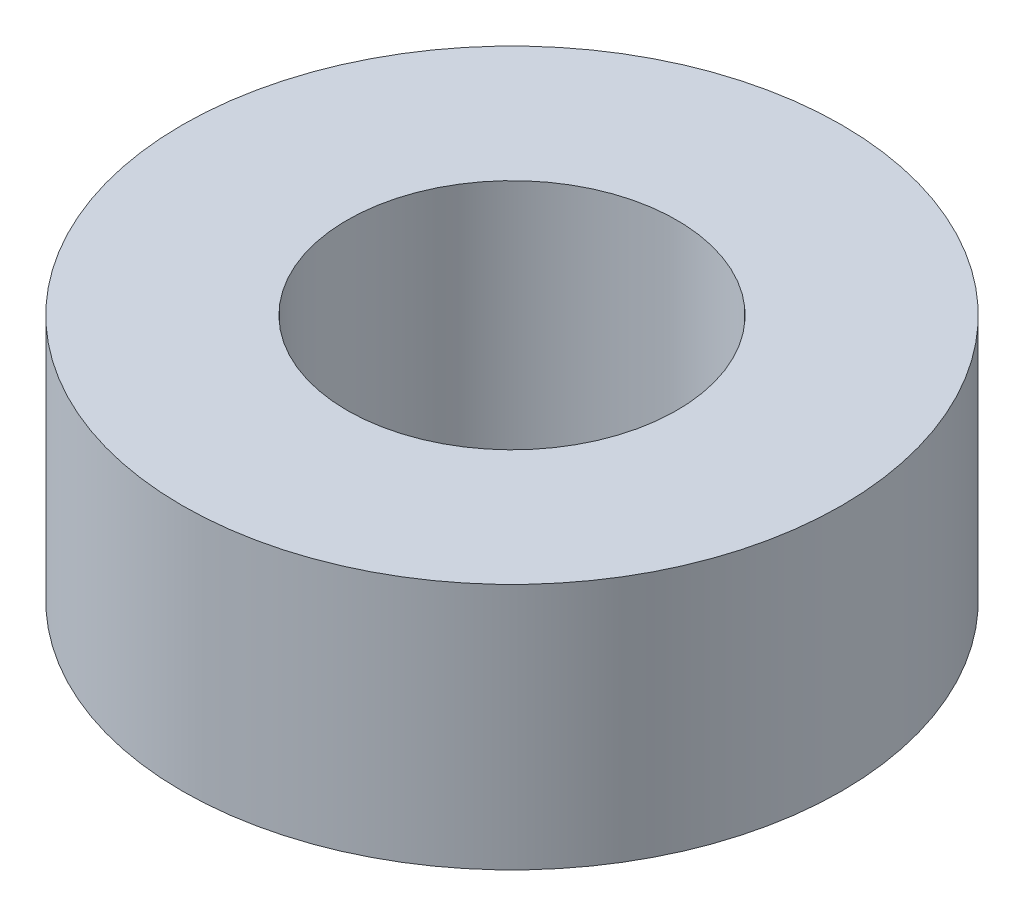
SolidWorks part; units mm, degrees
ref_plane "Plan de face" through (0, 0, 0) normal (0, 0, 1) x (1, 0, 0)
ref_plane "Plan de dessus" through (0, 0, 0) normal (0, 1, 0) x (1, 0, 0)
ref_plane "Plan de droite" through (0, 0, 0) normal (1, 0, 0) x (0, 0, -1)
sketch "Esquisse1" plane through (0, 0, 0) normal (0, 1, 0) x (1, 0, 0)
  circle A0 centre (0, 0) radius 2
  circle A1 centre (0, 0) radius 4
  dimension "D1" = 4
  dimension "D2" = 8
extrude "Boss.-Extru.1" add sketch "Esquisse1" along normal blind 3
